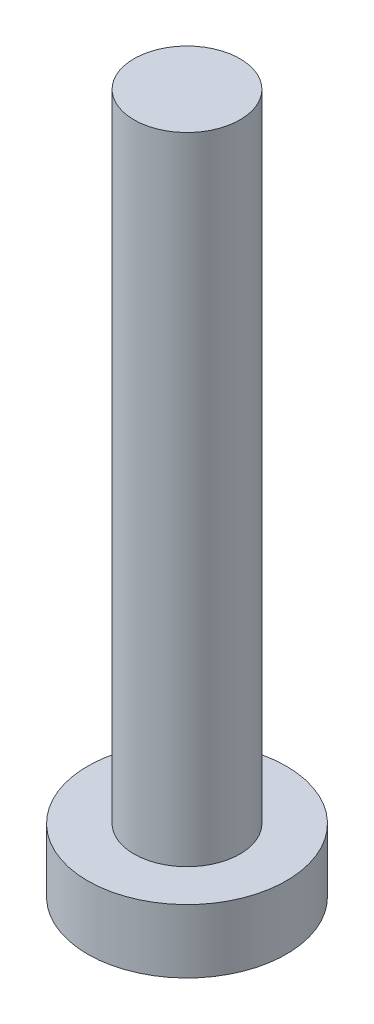
SolidWorks part; units mm, degrees
ref_plane "Front Plane" through (0, 0, 0) normal (0, 0, 1) x (1, 0, 0)
ref_plane "Top Plane" through (0, 0, 0) normal (0, 1, 0) x (1, 0, 0)
ref_plane "Right Plane" through (0, 0, 0) normal (1, 0, 0) x (0, 0, -1)
other "Configuration Table"
sketch "Sketch1" plane through (0, 0, 0) normal (0, 1, 0) x (1, 0, 0)
  line L1 (0.866, 0) -> (0.433, 0.75)
  line L2 (0.433, 0.75) -> (-0.433, 0.75)
  line L3 (-0.433, 0.75) -> (-0.866, 0)
  line L4 (-0.866, 0) -> (-0.433, -0.75)
  line L5 (-0.433, -0.75) -> (0.433, -0.75)
  line L6 (0.433, -0.75) -> (0.866, 0)
  circle A0 centre (0, 0) radius 1.875
  circle A1 centre (0, 0) radius 0.75 construction
  dimension "D1" = 3.75
  dimension "D2" = 1.5
extrude "Boss-Extrude1" add sketch "Sketch1" along normal blind 1.2
sketch "Sketch2" plane through (0, 1.2, 0) normal (0, 1, 0) x (1, 0, 0)
  circle A0 centre (0, 0) radius 1
  dimension "D1" = 2
extrude "Boss-Extrude2" add sketch "Sketch2" along normal blind 12
sketch "Sketch3" [suppressed] plane through (0, 13.2, 0) normal (0, 1, 0) x (1, 0, 0)
  circle A1 centre (0, 0) radius 1
  circle A2 centre (0, 0) radius 1
  dimension "D1" = 0
extrude "Cut-Extrude1" [suppressed] cut sketch "Sketch3" against normal blind 8
sketch "Sketch4" [suppressed] plane through (0, 13.2, 0) normal (0, 1, 0) x (1, 0, 0)
  circle A1 centre (0, 0) radius 1
  circle A2 centre (0, 0) radius 1
  dimension "D1" = 0
extrude "Cut-Extrude2" [suppressed] cut sketch "Sketch4" against normal blind 6
